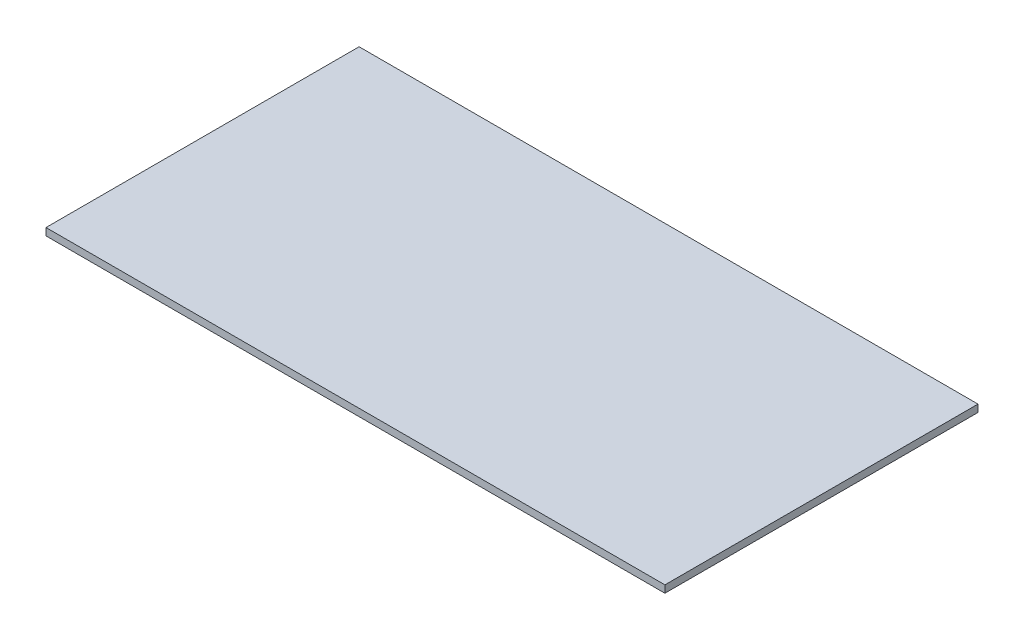
SolidWorks part; units mm, degrees
material "AISI 304"
ref_plane "Piano frontale" through (0, 0, 0) normal (0, 0, 1) x (1, 0, 0)
ref_plane "Piano superiore" through (0, 0, 0) normal (0, 1, 0) x (1, 0, 0)
ref_plane "Piano destro" through (0, 0, 0) normal (1, 0, 0) x (0, 0, -1)
sketch "Schizzo1" plane through (0, 0, 0) normal (0, 1, 0) x (1, 0, 0)
  line L1 (425, -215) -> (-425, -215)
  line L2 (425, -215) -> (425, 215)
  line L3 (425, 215) -> (-425, 215)
  line L4 (-425, -215) -> (-425, 215)
  line L5 (425, -215) -> (-425, 215) construction
  line L6 (425, 215) -> (-425, -215) construction
  point P0 (0, 0)
extrude "Estrusione-Estrusione1" add sketch "Schizzo1" along normal blind 10
